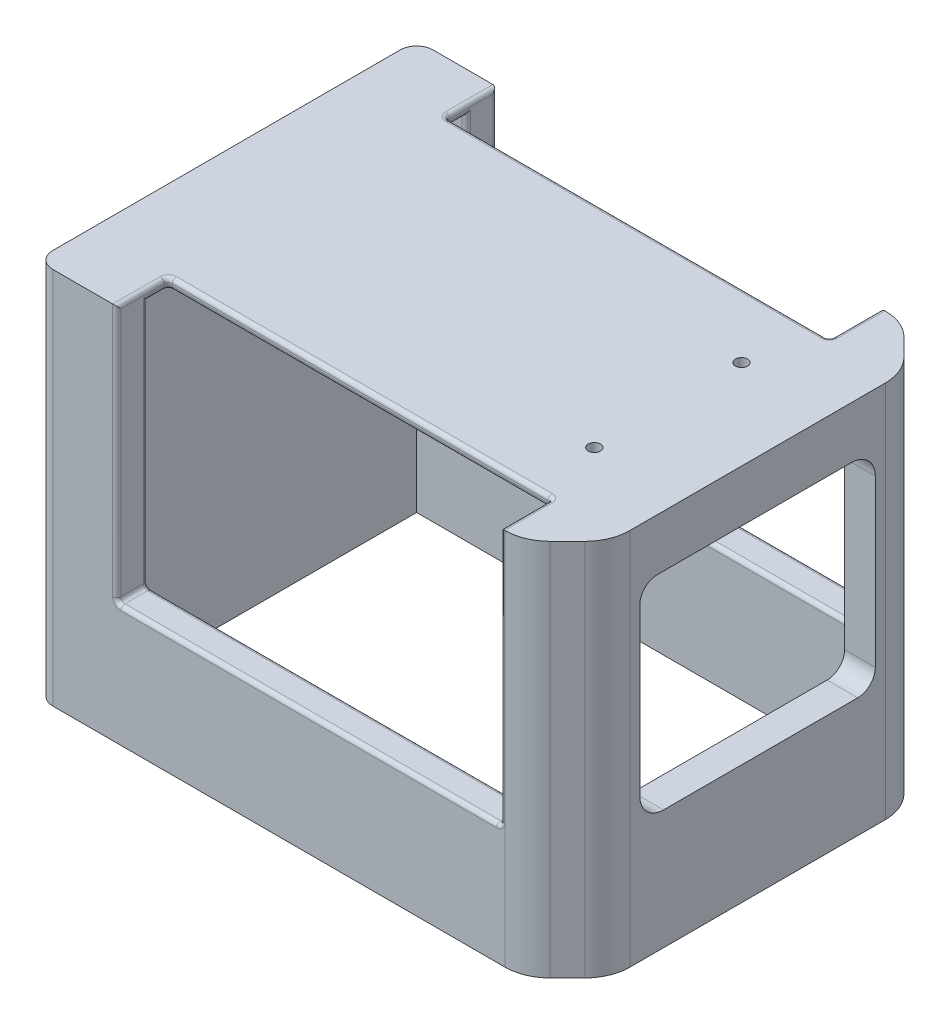
SolidWorks part; units mm, degrees
ref_plane "Alzado" through (0, 0, 0) normal (0, 0, 1) x (1, 0, 0)
ref_plane "Planta" through (0, 0, 0) normal (0, 1, 0) x (1, 0, 0)
ref_plane "Vista lateral" through (0, 0, 0) normal (1, 0, 0) x (0, 0, -1)
ref_plane "Plano1" through (0, 95.6, 0) normal (0, 1, 0) x (1, 0, 0)
sketch "Croquis1" plane through (0, 95.6, 0) normal (0, 1, 0) x (1, 0, 0)
  line L0 (225.1213, 37.6213) -> (220.8787, 33.3787) construction
  line L1 (220, 31.2574) -> (220, -31.2574) construction
  line L2 (220.8787, -33.3787) -> (225.1213, -37.6213) construction
  line L3 (329.8787, -37.6213) -> (334.1213, -33.3787) construction
  line L4 (334.1213, 33.3787) -> (329.8787, 37.6213) construction
  line L5 (225.1213, 37.6213) -> (220.8787, 33.3787) construction
  line L6 (220, 31.2574) -> (220, -31.2574) construction
  line L7 (220.8787, -33.3787) -> (225.1213, -37.6213) construction
  line L8 (329.8787, -37.6213) -> (334.1213, -33.3787) construction
  line L9 (334.1213, 33.3787) -> (329.8787, 37.6213) construction
  line L10 (227.2426, 38.5) -> (327.7574, 38.5) construction
  line L11 (335, 31.2574) -> (335, -31.2574) construction
  line L12 (327.7574, -38.5) -> (227.2426, -38.5) construction
  line L16 (327.7574, -46.5) -> (227.2426, -46.5)
  line L17 (335.5355, -43.2782) -> (339.7782, -39.0355)
  line L18 (343, 31.2574) -> (343, -31.2574)
  line L19 (339.7782, 39.0355) -> (335.5355, 43.2782)
  line L20 (227.2426, 46.5) -> (327.7574, 46.5)
  line L21 (227.2426, 46.5) -> (217.1, 46.5)
  line L22 (213.1, 36.2242) -> (213.1, 31.0242) construction
  line L23 (213.1, 42.5) -> (213.1, -42.5)
  line L24 (227.2426, -46.5) -> (217.1, -46.5)
  line L26 (219.4645, 43.2782) -> (215.2218, 39.0355) construction
  line L27 (212, 31.2574) -> (212, -31.2574) construction
  line L28 (215.2218, -39.0355) -> (219.4645, -43.2782) construction
  arc A0 (227.2426, 38.5) -> (225.1213, 37.6213) centre (227.2426, 35.5) ccw construction
  arc A1 (220.8787, 33.3787) -> (220, 31.2574) centre (223, 31.2574) ccw construction
  arc A2 (220, -31.2574) -> (220.8787, -33.3787) centre (223, -31.2574) ccw construction
  arc A3 (225.1213, -37.6213) -> (227.2426, -38.5) centre (227.2426, -35.5) ccw construction
  arc A4 (327.7574, -38.5) -> (329.8787, -37.6213) centre (327.7574, -35.5) ccw construction
  arc A5 (334.1213, -33.3787) -> (335, -31.2574) centre (332, -31.2574) ccw construction
  arc A6 (335, 31.2574) -> (334.1213, 33.3787) centre (332, 31.2574) ccw construction
  arc A7 (329.8787, 37.6213) -> (327.7574, 38.5) centre (327.7574, 35.5) ccw construction
  arc A8 (227.2426, 38.5) -> (225.1213, 37.6213) centre (227.2426, 35.5) ccw construction
  arc A9 (220.8787, 33.3787) -> (220, 31.2574) centre (223, 31.2574) ccw construction
  arc A10 (220, -31.2574) -> (220.8787, -33.3787) centre (223, -31.2574) ccw construction
  arc A11 (225.1213, -37.6213) -> (227.2426, -38.5) centre (227.2426, -35.5) ccw construction
  arc A12 (327.7574, -38.5) -> (329.8787, -37.6213) centre (327.7574, -35.5) ccw construction
  arc A13 (334.1213, -33.3787) -> (335, -31.2574) centre (332, -31.2574) ccw construction
  arc A14 (335, 31.2574) -> (334.1213, 33.3787) centre (332, 31.2574) ccw construction
  arc A15 (329.8787, 37.6213) -> (327.7574, 38.5) centre (327.7574, 35.5) ccw construction
  arc A19 (327.7574, -46.5) -> (335.5355, -43.2782) centre (327.7574, -35.5) ccw
  arc A20 (339.7782, -39.0355) -> (343, -31.2574) centre (332, -31.2574) ccw
  arc A21 (343, 31.2574) -> (339.7782, 39.0355) centre (332, 31.2574) ccw
  arc A22 (335.5355, 43.2782) -> (327.7574, 46.5) centre (327.7574, 35.5) ccw
  arc A24 (227.2426, 46.5) -> (219.4645, 43.2782) centre (227.2426, 35.5) ccw construction
  arc A25 (215.2218, 39.0355) -> (212, 31.2574) centre (223, 31.2574) ccw construction
  arc A26 (212, -31.2574) -> (215.2218, -39.0355) centre (223, -31.2574) ccw construction
  arc A27 (219.4645, -43.2782) -> (227.2426, -46.5) centre (227.2426, -35.5) ccw construction
  arc A28 (213.1, -42.5) -> (217.1, -46.5) centre (217.1, -42.5) ccw
  arc A29 (217.1, 46.5) -> (213.1, 42.5) centre (217.1, 42.5) ccw
  point P56 (213.1, 46.5)
  dimension "D2" = 4
  dimension "D1" = 8
extrude "Saliente-Extruir1" add sketch "Croquis1" along normal blind 2.5
sketch "Croquis2" plane through (0, 95.6, 0) normal (0, -1, 0) x (1, 0, 0)
  line L16 (213.1, 42.5) -> (213.1, -42.5)
  line L17 (213.1, 42.5) -> (213.1, -42.5)
  line L19 (327.7574, 46.5) -> (217.1, 46.5)
  line L20 (339.7782, 39.0355) -> (335.5355, 43.2782)
  line L21 (343, -31.2574) -> (343, 31.2574)
  line L22 (335.5355, -43.2782) -> (339.7782, -39.0355)
  line L23 (217.1, -46.5) -> (327.7574, -46.5)
  line L27 (327.7574, 46.5) -> (217.1, 46.5)
  line L28 (339.7782, 39.0355) -> (335.5355, 43.2782)
  line L29 (343, -31.2574) -> (343, 31.2574)
  line L30 (335.5355, -43.2782) -> (339.7782, -39.0355)
  line L31 (217.1, -46.5) -> (327.7574, -46.5)
  line L37 (220.6, 39) -> (220.6, -39)
  line L38 (220.6, 39) -> (220.6, -39)
  line L43 (327.7574, 39) -> (220.6, 39)
  line L44 (334.4749, 33.7322) -> (330.2322, 37.9749)
  line L45 (335.5, -31.2574) -> (335.5, 31.2574)
  line L46 (330.2322, -37.9749) -> (334.4749, -33.7322)
  line L47 (220.6, -39) -> (327.7574, -39)
  line L51 (327.7574, 39) -> (220.6, 39)
  line L52 (334.4749, 33.7322) -> (330.2322, 37.9749)
  line L53 (335.5, -31.2574) -> (335.5, 31.2574)
  line L54 (330.2322, -37.9749) -> (334.4749, -33.7322)
  line L55 (220.6, -39) -> (327.7574, -39)
  arc A6 (330.2322, 37.9749) -> (327.7574, 39) centre (327.7574, 35.5) ccw
  arc A7 (330.2322, 37.9749) -> (327.7574, 39) centre (327.7574, 35.5) ccw
  arc A8 (335.5, 31.2574) -> (334.4749, 33.7322) centre (332, 31.2574) ccw
  arc A9 (335.5, 31.2574) -> (334.4749, 33.7322) centre (332, 31.2574) ccw
  arc A10 (334.4749, -33.7322) -> (335.5, -31.2574) centre (332, -31.2574) ccw
  arc A11 (334.4749, -33.7322) -> (335.5, -31.2574) centre (332, -31.2574) ccw
  arc A12 (327.7574, -39) -> (330.2322, -37.9749) centre (327.7574, -35.5) ccw
  arc A13 (327.7574, -39) -> (330.2322, -37.9749) centre (327.7574, -35.5) ccw
  arc A16 (213.1, -42.5) -> (217.1, -46.5) centre (217.1, -42.5) ccw
  arc A17 (213.1, -42.5) -> (217.1, -46.5) centre (217.1, -42.5) ccw
  arc A18 (217.1, 46.5) -> (213.1, 42.5) centre (217.1, 42.5) ccw
  arc A19 (217.1, 46.5) -> (213.1, 42.5) centre (217.1, 42.5) ccw
  arc A20 (335.5355, 43.2782) -> (327.7574, 46.5) centre (327.7574, 35.5) ccw
  arc A21 (343, 31.2574) -> (339.7782, 39.0355) centre (332, 31.2574) ccw
  arc A22 (339.7782, -39.0355) -> (343, -31.2574) centre (332, -31.2574) ccw
  arc A23 (327.7574, -46.5) -> (335.5355, -43.2782) centre (327.7574, -35.5) ccw
  arc A28 (335.5355, 43.2782) -> (327.7574, 46.5) centre (327.7574, 35.5) ccw
  arc A29 (343, 31.2574) -> (339.7782, 39.0355) centre (332, 31.2574) ccw
  arc A30 (339.7782, -39.0355) -> (343, -31.2574) centre (332, -31.2574) ccw
  arc A31 (327.7574, -46.5) -> (335.5355, -43.2782) centre (327.7574, -35.5) ccw
  dimension "D1" = 0
  dimension "D2" = 7.5
extrude "Saliente-Extruir2" add sketch "Croquis2" along normal blind 90
sketch "Croquis3" plane through (343, 0, 0) normal (1, 0, 0) x (0, 0, -1)
  line L0 (-28.1, 81.1) -> (-28.1, 40.6) construction
  line L1 (-23, 35.5) -> (24.5, 35.5) construction
  line L2 (28.1, 39.1) -> (28.1, 79.6) construction
  line L3 (23, 84.7) -> (-24.5, 84.7) construction
  line L4 (-28.1, 81.1) -> (-28.1, 40.6) construction
  line L5 (-23, 35.5) -> (24.5, 35.5) construction
  line L6 (28.1, 39.1) -> (28.1, 79.6) construction
  line L7 (23, 84.7) -> (-24.5, 84.7) construction
  line L16 (23, 85.4) -> (-24.5, 85.4)
  line L17 (-28.8, 81.1) -> (-28.8, 40.6)
  line L18 (-23, 34.8) -> (24.5, 34.8)
  line L19 (28.8, 39.1) -> (28.8, 79.6)
  line L20 (23, 85.4) -> (-24.5, 85.4)
  line L21 (-28.8, 81.1) -> (-28.8, 40.6)
  line L22 (-23, 34.8) -> (24.5, 34.8)
  line L23 (28.8, 39.1) -> (28.8, 79.6)
  arc A0 (-28.1, 40.6) -> (-23, 35.5) centre (-23, 40.6) ccw construction
  arc A1 (24.5, 35.5) -> (28.1, 39.1) centre (24.5, 39.1) ccw construction
  arc A2 (28.1, 79.6) -> (23, 84.7) centre (23, 79.6) ccw construction
  arc A3 (-24.5, 84.7) -> (-28.1, 81.1) centre (-24.5, 81.1) ccw construction
  arc A4 (-28.1, 40.6) -> (-23, 35.5) centre (-23, 40.6) ccw construction
  arc A5 (24.5, 35.5) -> (28.1, 39.1) centre (24.5, 39.1) ccw construction
  arc A6 (28.1, 79.6) -> (23, 84.7) centre (23, 79.6) ccw construction
  arc A7 (-24.5, 84.7) -> (-28.1, 81.1) centre (-24.5, 81.1) ccw construction
  arc A16 (-24.5, 85.4) -> (-28.8, 81.1) centre (-24.5, 81.1) ccw
  arc A17 (-28.8, 40.6) -> (-23, 34.8) centre (-23, 40.6) ccw
  arc A18 (24.5, 34.8) -> (28.8, 39.1) centre (24.5, 39.1) ccw
  arc A19 (28.8, 79.6) -> (23, 85.4) centre (23, 79.6) ccw
  arc A20 (-24.5, 85.4) -> (-28.8, 81.1) centre (-24.5, 81.1) ccw
  arc A21 (-28.8, 40.6) -> (-23, 34.8) centre (-23, 40.6) ccw
  arc A22 (24.5, 34.8) -> (28.8, 39.1) centre (24.5, 39.1) ccw
  arc A23 (28.8, 79.6) -> (23, 85.4) centre (23, 79.6) ccw
  dimension "D1" = 1
extrude "Cortar-Extruir2" cut sketch "Croquis3" against normal up to next
sketch "Croquis4" plane through (0, 98.1, 0) normal (0, 1, 0) x (1, 0, 0)
  line L0 (324.7574, -38.5) -> (326.5574, -38.5) construction
  line L4 (232.7574, -33.9) -> (232.7574, -38.5)
  line L5 (232.7574, -33.9) -> (326.6574, -33.9)
  line L6 (326.6574, -33.9) -> (326.6574, -38.5)
  line L7 (322.1574, -34.4) -> (319.1574, -34.4) construction
  line L8 (326.2574, -34.4) -> (326.2574, -36.5) construction
  line L9 (326.6574, -38.5) -> (326.6574, -46.5)
  line L10 (217.1, -46.5) -> (327.7574, -46.5) construction
  line L11 (326.6574, -46.5) -> (232.7574, -46.5)
  line L12 (232.7574, -46.5) -> (232.7574, -38.5)
  line L13 (-55, 0) -> (55, 0) construction
  line L14 (326.6574, 46.5) -> (232.7574, 46.5)
  line L15 (326.6574, 38.5) -> (326.6574, 46.5)
  line L16 (326.6574, 33.9) -> (326.6574, 38.5)
  line L17 (232.7574, 33.9) -> (326.6574, 33.9)
  line L18 (232.7574, 33.9) -> (232.7574, 38.5)
  line L19 (232.7574, 46.5) -> (232.7574, 38.5)
  dimension "D1" = 0.5
  dimension "D2" = 0.4
extrude "Cortar-Extruir4" cut sketch "Croquis4" against normal blind 63
fillet "Redondeo1" radius 1 32 edges at (279.7074, 95.6, -33.9) (279.7074, 98.1, -33.9) (279.7074, 35.1, -46.5) (279.7074, 35.1, -39) (279.7074, 35.1, 39) (279.7074, 35.1, 46.5) (326.6574, 35.1, -42.75) (326.6574, 66.6, -46.5) (326.6574, 98.1, -40.2) (326.6574, 96.85, -33.9) (326.6574, 95.6, -36.45) (326.6574, 65.35, -39) (232.7574, 95.6, -36.45) (232.7574, 96.85, -33.9) (232.7574, 98.1, -40.2) (232.7574, 66.6, -46.5) (232.7574, 35.1, -42.75) (232.7574, 65.35, -39) (326.6574, 95.6, 36.45) (326.6574, 98.1, 40.2) (326.6574, 66.6, 46.5) (326.6574, 35.1, 42.75) (326.6574, 65.35, 39) (232.7574, 35.1, 42.75) (232.7574, 66.6, 46.5) (232.7574, 98.1, 40.2) (232.7574, 95.6, 36.45) (232.7574, 65.35, 39) (279.7074, 95.6, 33.9) (232.7574, 96.85, 33.9) (279.7074, 98.1, 33.9) (326.6574, 96.85, 33.9)
sketch "Croquis5" plane through (213.1, 0, 0) normal (-1, 0, 0) x (0, 0, 1)
  line L0 (-19.6758, 71.7242) -> (-19.6758, 48.4758) construction
  line L1 (-19.6758, 71.7242) -> (-19.6758, 48.4758)
  line L2 (-31.0242, 77.7242) -> (-25.6758, 77.7242) construction
  line L3 (-25.6758, 42.4758) -> (-31.0242, 42.4758) construction
  line L12 (-31.0242, 77.7242) -> (-25.6758, 77.7242)
  line L13 (-25.6758, 42.4758) -> (-31.0242, 42.4758)
  line L14 (-37.0242, 71.7242) -> (-37.0242, 48.4758)
  arc A0 (-19.6758, 71.7242) -> (-25.6758, 77.7242) centre (-25.6758, 71.7242) ccw construction
  arc A1 (-19.6758, 71.7242) -> (-25.6758, 77.7242) centre (-25.6758, 71.7242) ccw
  arc A2 (-37.0242, 48.4758) -> (-31.0242, 42.4758) centre (-31.0242, 48.4758) ccw construction
  arc A3 (-25.6758, 42.4758) -> (-19.6758, 48.4758) centre (-25.6758, 48.4758) ccw construction
  arc A4 (-31.0242, 77.7242) -> (-37.0242, 71.7242) centre (-31.0242, 71.7242) ccw construction
  arc A5 (-37.0242, 48.4758) -> (-31.0242, 42.4758) centre (-31.0242, 48.4758) ccw
  arc A6 (-25.6758, 42.4758) -> (-19.6758, 48.4758) centre (-25.6758, 48.4758) ccw
  arc A7 (-31.0242, 77.7242) -> (-37.0242, 71.7242) centre (-31.0242, 71.7242) ccw
extrude "Cortar-Extruir5" cut sketch "Croquis5" against normal up to next
sketch "Croquis7" plane through (0, 98.1, 0) normal (0, 1, 0) x (1, 0, 0)
  circle A0 centre (321.08, 18.0005) radius 1.5
  circle A1 centre (321.08, -18.0005) radius 1.5
  dimension "D1" = 3
  dimension "D2" = 3
extrude "Cortar-Extruir6" cut sketch "Croquis7" against normal blind 5
